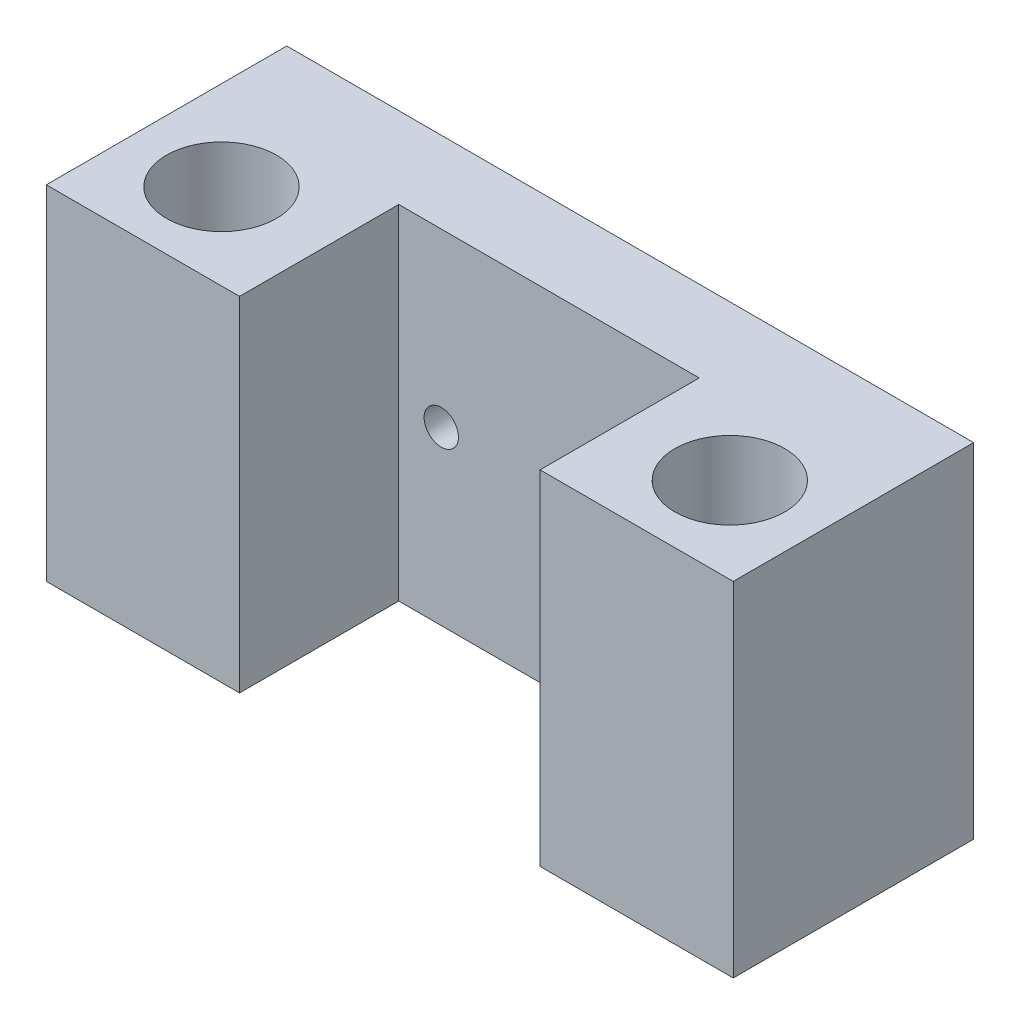
SolidWorks part; units mm, degrees
ref_plane "Front Plane" through (0, 0, 0) normal (0, 0, 1) x (1, 0, 0)
ref_plane "Top Plane" through (0, 0, 0) normal (0, 1, 0) x (1, 0, 0)
ref_plane "Right Plane" through (0, 0, 0) normal (1, 0, 0) x (0, 0, -1)
sketch "Sketch3" plane through (0, 0, 0) normal (0, 0, 1) x (1, 0, 0)
  line L1 (-50, -25) -> (50, -25)
  line L2 (-50, -25) -> (-50, 25)
  line L3 (-50, 25) -> (50, 25)
  line L4 (50, -25) -> (50, 25)
  line L5 (-50, -25) -> (50, 25) construction
  line L6 (-50, 25) -> (50, -25) construction
  point P0 (0, 0)
extrude "Boss-Extrude1" add sketch "Sketch3" along normal blind 25
sketch "Sketch5" plane through (0, 25, 0) normal (0, 1, 0) x (1, 0, 0)
  line L11 (-21.873, -25) -> (-21.873, -1.8248)
  line L12 (50, -25) -> (-50, -25) construction
  line L16 (-21.873, -1.8248) -> (21.873, -1.8248)
  line L17 (21.873, -1.8248) -> (21.873, -25)
  line L18 (21.873, -25) -> (-21.873, -25)
  circle A1 centre (37, -12.5) radius 8
  circle A2 centre (-37, -12.5) radius 8
  point P12 (0, -5)
  point P16 (0, -12.5)
extrude "Cut-Extrude1" cut sketch "Sketch5" against normal through all
sketch "Sketch7" plane through (0, 0, 0) normal (0, 0, -1) x (-1, 0, 0)
  circle A0 centre (32.5, 9.25) radius 2.5
  circle A1 centre (32.5, -9.25) radius 2.5
  circle A2 centre (-32.5, -9.25) radius 2.5
  circle A3 centre (-32.5, 9.25) radius 2.5
  point P8 (0, 0)
  point P11 (32.5, 0)
  point P14 (0, 0)
  point P16 (0, 0)
  point P23 (0, 0)
  dimension "D1" = 5
  dimension "D2" = 18.5
extrude "Cut-Extrude4" cut sketch "Sketch7" against normal blind 10
sketch "Sketch8" plane through (0, 0, 0) normal (0, 0, -1) x (-1, 0, 0)
  line L0 (-50, 25) -> (50, 25)
  line L1 (50, 25) -> (50, -25)
  line L2 (50, -25) -> (-50, -25)
  line L3 (-50, -25) -> (-50, 25)
  circle A0 centre (-32.5, 9.25) radius 2.5
  circle A1 centre (-32.5, -9.25) radius 2.5
  circle A2 centre (32.5, -9.25) radius 2.5
  circle A3 centre (32.5, 9.25) radius 2.5
extrude "Boss-Extrude2" add sketch "Sketch8" along normal blind 10
sketch "Sketch9" plane through (0, 0, 1.8248) normal (0, 0, 1) x (1, 0, 0)
  circle A0 centre (-15.68, 0) radius 2.5
  circle A1 centre (15.68, 0) radius 2.5
  point P8 (0, 0)
extrude "Cut-Extrude5" cut sketch "Sketch9" against normal blind 10
